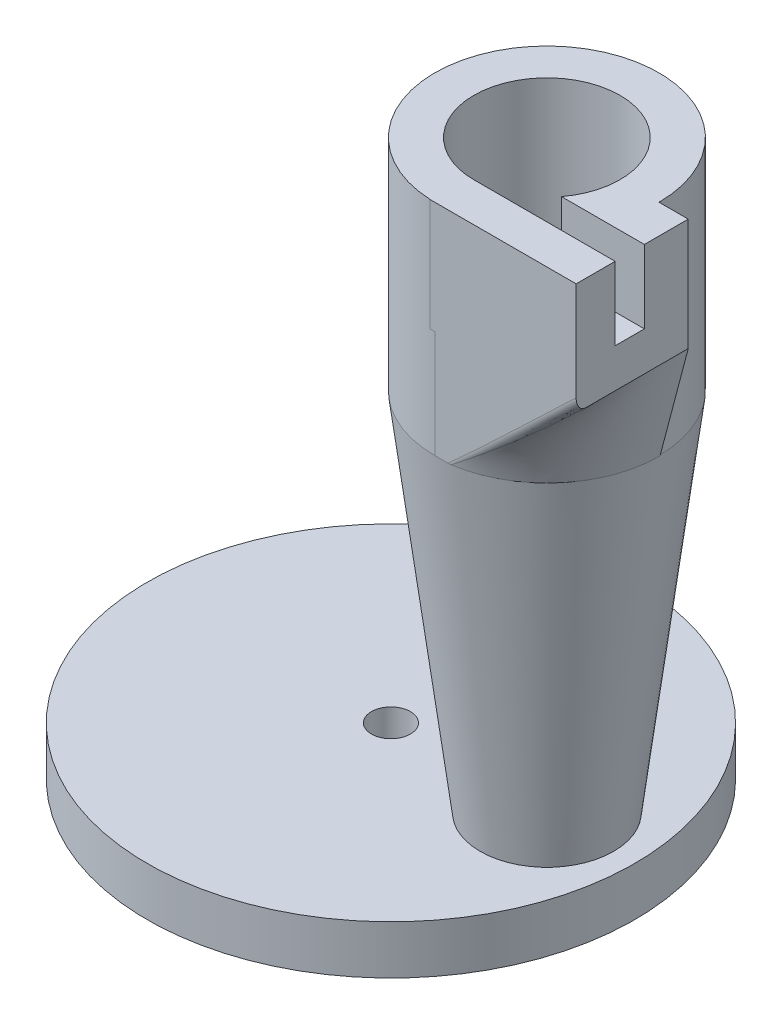
SolidWorks part; units mm, degrees
ref_plane "Front Plane" through (0, 0, 0) normal (0, 0, 1) x (1, 0, 0)
ref_plane "Top Plane" through (0, 0, 0) normal (0, 1, 0) x (1, 0, 0)
ref_plane "Right Plane" through (0, 0, 0) normal (1, 0, 0) x (0, 0, -1)
sketch "Sketch1" plane through (0, 0, 0) normal (0, 0, 1) x (1, 0, 0)
  line L0 (2.815, 0) -> (7.5, 37.7473)
  line L1 (55, 0) -> (-55, 0) construction
  line L2 (7.5, 37.7473) -> (7.5, 60)
  line L3 (7.5, 60) -> (11.5, 60)
  line L4 (11.5, 60) -> (11.5, 37.5)
  line L5 (11.5, 37.5) -> (6.8457, 0)
  line L6 (6.8457, 0) -> (8, 0)
  line L7 (0, -55) -> (0, 55) construction
  line L8 (0, 0) -> (0, 64.9115) construction
  line L9 (2.815, -4.9998) -> (2.815, -5)
  line L10 (2.815, -4.9998) -> (2.815, 0)
  line L11 (2.815, -5) -> (8, -5)
  line L12 (8, 0) -> (8, -5)
  dimension "D1" = 7.5
  dimension "D2" = 4
  dimension "D3" = 4
  dimension "D4" = 22.5
  dimension "D5" = 37.5
  dimension "D6" = 2.815
  dimension "D7" = 5
  dimension "D8" = 8
revolve "Revolve1" add sketch "Sketch1" angle 360 about L8
ref_plane "Plane1" through (0, 37.5, 0) normal (0, 1, 0) x (1, 0, 0)
ref_plane "Plane2" through (14.5, 0, 0) normal (1, 0, 0) x (0, 0, -1)
ref_plane "Plane3" through (0, 0, 7.5) normal (0, 0, 1) x (1, 0, 0)
sketch "Sketch8" plane through (14.5, 0, 0) normal (1, 0, 0) x (0, 0, -1)
  line L0 (-11.5, 60) -> (-11.5, 48.5)
  line L1 (11.5, 60) -> (-11.5, 60) construction
  line L2 (-11.5, 48.5) -> (0, 48.5)
  line L3 (0, 48.5) -> (0, 60)
  line L4 (-4.5, 60) -> (0, 60)
  line L5 (-7.5, 60) -> (-7.5, 52.5)
  line L6 (-7.5, 52.5) -> (-4.5, 52.5)
  line L7 (-4.5, 52.5) -> (-4.5, 60)
  line L8 (-11.5, 60) -> (-7.5, 60)
  line L9 (-7.5, 16.5) -> (-7.5, -16.5) construction
  line L10 (0, 55) -> (0, -55) construction
  dimension "D1" = 4
  dimension "D3" = 4
  dimension "D4" = 7.5
  dimension "D6" = 3
extrude "Boss-Extrude2" add sketch "Sketch8" against normal blind 15 contours L0 L2 L3
sketch "Sketch9" plane through (14.5, 0, 0) normal (1, 0, 0) x (0, 0, -1)
  line L0 (-4.5, 60) -> (-4.5, 52.5) construction
  line L1 (-4.5, 60) -> (-7.5, 60)
  line L2 (-4.5, 60) -> (-4.5, 52.5)
  line L3 (-4.5, 52.5) -> (-7.5, 52.5)
  line L4 (-7.5, 60) -> (-7.5, 52.5)
  line L5 (-4.5, 60) -> (-7.5, 60) construction
extrude "Cut-Extrude2" cut sketch "Sketch9" against normal blind 14.5
sketch "Sketch10" plane through (0, 60, 0) normal (0, 1, 0) x (1, 0, 0)
  circle A0 centre (0, 0) radius 7.5
  arc A1 (7.5, 0) -> (0, -7.5) centre (0, 0) ccw construction
extrude "Cut-Extrude3" cut sketch "Sketch10" against normal blind 19
sketch "Sketch11" plane through (0, 48.5, 0) normal (0, -1, 0) x (1, 0, 0)
  line L0 (0, 11.5) -> (14.5, 11.5) construction
  line L1 (0, 11.5) -> (14.5, 11.5)
  line L2 (14.5, -16.5) -> (14.5, 16.5) construction
  line L3 (14.5, 11.5) -> (14.5, 0)
  line L4 (14.5, 0) -> (11.5, 0)
  line L5 (55, 0) -> (-55, 0) construction
  arc A0 (11.5, 0) -> (0, 11.5) centre (0, 0) ccw
  arc A1 (11.5, 0) -> (0, 11.5) centre (0, 0) ccw construction
sketch "Sketch12" plane through (0, 37.5, 0) normal (0, 1, 0) x (1, 0, 0)
  line L0 (0, -11.5) -> (14.5, -11.5) construction
  line L2 (14.5, 0) -> (11.5, 0) construction
  line L3 (0, -11.5) -> (1.5199, -11.5)
  line L4 (11.6, 0) -> (11.5, 0)
  arc A0 (11.5, 0) -> (0, -11.5) centre (0, 0) cw
  arc A1 (0, -11.5) -> (11.5, 0) centre (0, 0) ccw construction
  arc A2 (11.6, 0) -> (1.5199, -11.5) centre (0, 0) cw
  dimension "D1" = 0.1
loft "Loft4" add profiles "Sketch11", "Sketch12"
fillet "Fillet2" radius 1 2 edges
sketch "Sketch13" plane through (0, -5, 0) normal (0, -1, 0) x (1, 0, 0)
  circle A0 centre (-16, 0) radius 25
  circle A1 centre (0, 0) radius 6.6 construction
  circle A2 centre (0, 0) radius 2.815
  circle A3 centre (0, 0) radius 2.815 construction
  circle A4 centre (-16, 0) radius 2
  dimension "D1" = 13.2
  dimension "D2" = 50
  dimension "D4" = 4
  dimension "D3" = 16
extrude "Boss-Extrude3" add sketch "Sketch13" against normal blind 5
